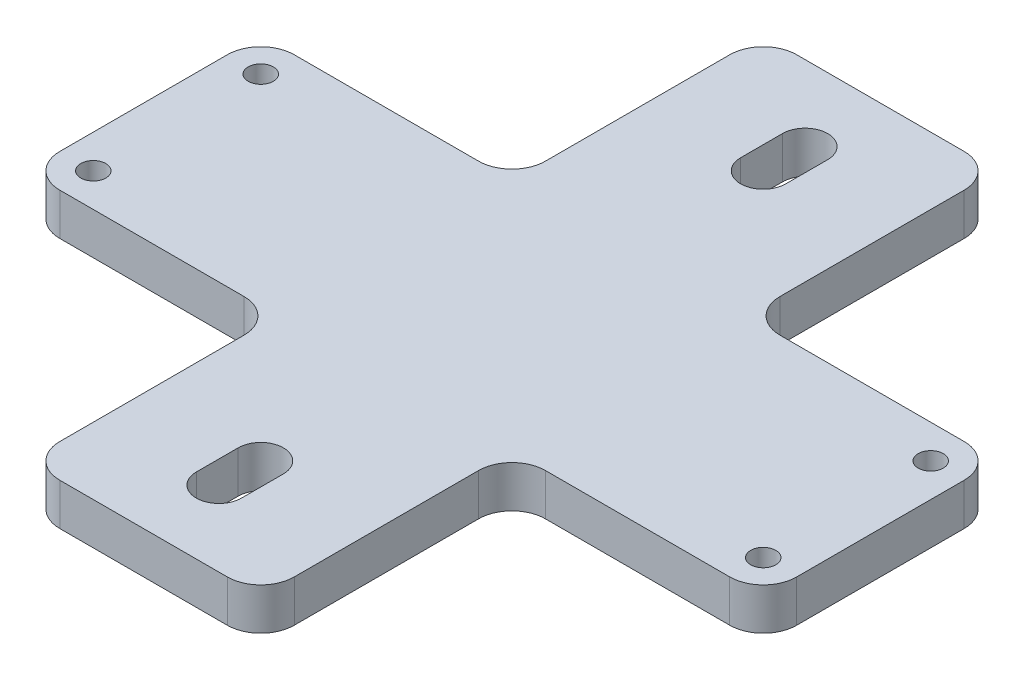
SolidWorks part; units mm, degrees
ref_plane "前视基准面" through (0, 0, 0) normal (0, 0, 1) x (1, 0, 0)
ref_plane "上视基准面" through (0, 0, 0) normal (0, 1, 0) x (1, 0, 0)
ref_plane "右视基准面" through (0, 0, 0) normal (1, 0, 0) x (0, 0, -1)
sketch "草图1" plane through (0, 0, 0) normal (0, 1, 0) x (1, 0, 0)
  line L1 (0, 30) -> (0, 35)
  line L2 (0, 35) -> (0, 30) construction
  line L3 (2.7, 35) -> (2.7, 30)
  line L4 (-44, 10) -> (-44, -10)
  line L10 (44, 10) -> (44, -10)
  line L11 (40, 14) -> (18, 14)
  line L12 (-2.7, 35) -> (-2.7, 30)
  line L13 (0, -35) -> (0, -30) construction
  line L14 (-2.7, -35) -> (-2.7, -30)
  line L15 (2.7, -35) -> (2.7, -30)
  line L16 (14, -40) -> (14, -18)
  line L17 (10, -44) -> (-10, -44)
  line L18 (-14, 40) -> (-14, 18)
  line L19 (10, 44) -> (-10, 44)
  line L20 (-40, -14) -> (-18, -14)
  line L21 (-44, -10) -> (-44, 10)
  line L22 (40, 14) -> (18, 14)
  line L23 (44, -10) -> (44, 10)
  line L24 (-14, 40) -> (-14, 18)
  line L25 (-10, 44) -> (10, 44)
  line L26 (14, -40) -> (14, -18)
  line L27 (-10, -44) -> (10, -44)
  line L29 (-14, -18) -> (-14, -40)
  line L30 (-18, 14) -> (-40, 14)
  line L31 (-18, 14) -> (-40, 14)
  line L32 (14, 18) -> (14, 40)
  line L33 (14, 18) -> (14, 40)
  line L34 (18, -14) -> (40, -14)
  line L35 (18, -14) -> (40, -14)
  circle A0 centre (40, 10) radius 1.5
  circle A1 centre (40, -10) radius 1.5
  circle A2 centre (-40, 10) radius 1.5
  circle A3 centre (-40, -10) radius 1.5
  arc A4 (-40, 14) -> (-44, 10) centre (-40, 10) ccw
  arc A5 (44, 10) -> (40, 14) centre (40, 10) ccw
  arc A6 (40, -14) -> (44, -10) centre (40, -10) ccw
  arc A7 (-44, -10) -> (-40, -14) centre (-40, -10) ccw
  arc A8 (2.7, 35) -> (-2.7, 35) centre (0, 35) ccw
  arc A9 (-2.7, 30) -> (2.7, 30) centre (0, 30) ccw
  arc A10 (-2.7, -35) -> (2.7, -35) centre (0, -35) ccw
  arc A11 (2.7, -30) -> (-2.7, -30) centre (0, -30) ccw
  arc A12 (10, -44) -> (14, -40) centre (10, -40) ccw
  arc A13 (-14, -40) -> (-10, -44) centre (-10, -40) ccw
  arc A14 (-10, 44) -> (-14, 40) centre (-10, 40) ccw
  arc A15 (14, 40) -> (10, 44) centre (10, 40) ccw
  arc A16 (-44, -10) -> (-40, -14) centre (-40, -10) ccw
  arc A17 (-40, 14) -> (-44, 10) centre (-40, 10) ccw
  arc A18 (44, 10) -> (40, 14) centre (40, 10) ccw
  arc A19 (40, -14) -> (44, -10) centre (40, -10) ccw
  arc A20 (-10, 44) -> (-14, 40) centre (-10, 40) ccw
  arc A21 (14, 40) -> (10, 44) centre (10, 40) ccw
  arc A22 (10, -44) -> (14, -40) centre (10, -40) ccw
  arc A23 (-14, -40) -> (-10, -44) centre (-10, -40) ccw
  arc A24 (-18, -14) -> (-14, -18) centre (-18, -18) cw
  arc A25 (-14, 18) -> (-18, 14) centre (-18, 18) cw
  arc A26 (18, 14) -> (14, 18) centre (18, 18) cw
  arc A27 (14, -18) -> (18, -14) centre (18, -18) cw
  point P3 (0, 32.5)
  point P9 (0, 0)
  point P30 (0, -32.5)
  point P36 (0, 0)
  point P73 (0, 0)
  point P87 (0, 0)
extrude "凸台-拉伸1" add sketch "草图1" along normal blind 5 contours L16 A27 L34 A6 L10 A5 L11 A26 L32 A15 L19 A14 L18 A25 L30 A4 L4 A7 L20 A24 L29 A13 L17 A12 A0 A1 A2 A3 A9 L12 A8 L3 A11 L15 A10 L14
